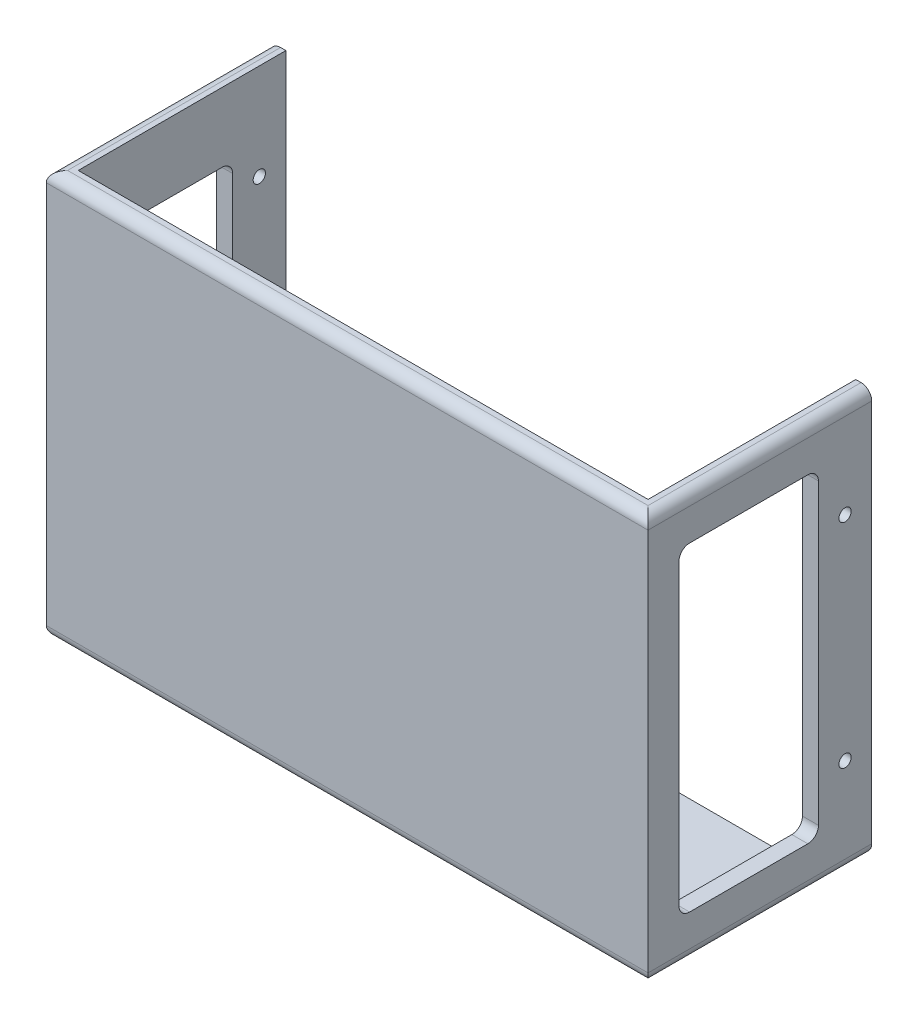
SolidWorks part; units mm, degrees
ref_plane "前视基准面" through (0, 0, 0) normal (0, 0, 1) x (1, 0, 0)
ref_plane "上视基准面" through (0, 0, 0) normal (0, 1, 0) x (1, 0, 0)
ref_plane "右视基准面" through (0, 0, 0) normal (1, 0, 0) x (0, 0, -1)
other "Configuration Table"
sketch "草图1" plane through (0, 0, 0) normal (0, 0, 1) x (1, 0, 0)
  line L0 (-56.5, 38) -> (56.5, 38)
  line L1 (-53.5, -35) -> (53.5, -35)
  line L2 (-53.5, -35) -> (-53.5, 35)
  line L3 (-53.5, 35) -> (53.5, 35)
  line L4 (53.5, -35) -> (53.5, 35)
  line L5 (-53.5, -35) -> (53.5, 35) construction
  line L6 (-53.5, 35) -> (53.5, -35) construction
  line L7 (56.5, -38) -> (56.5, 38)
  line L8 (-56.5, -38) -> (56.5, -38)
  line L9 (-56.5, -38) -> (-56.5, 38)
  point P0 (0, 0)
  dimension "D1" = 107
  dimension "D2" = 70
  dimension "D3" = 3
extrude "凸台-拉伸1" add sketch "草图1" along normal blind 40
sketch "草图2" plane through (0, 0, 40) normal (0, 0, 1) x (1, 0, 0)
  line L1 (-56.5, 38) -> (56.5, 38)
  line L2 (-56.5, 38) -> (-56.5, -38)
  line L3 (-56.5, -38) -> (56.5, -38)
  line L4 (56.5, 38) -> (56.5, -38)
extrude "凸台-拉伸2" add sketch "草图2" along normal blind 2
sketch "草图3" plane through (-56.5, 0, 0) normal (-1, 0, 0) x (0, 0, 1)
  line L0 (0, 0) -> (5, 0)
  line L1 (5, 0) -> (5, 20)
  circle A0 centre (5, 20) radius 1.05
  circle A1 centre (5, -20) radius 1.05
  dimension "D3" = 2.1
  dimension "D1" = 5
  dimension "D2" = 20
extrude "切除-拉伸1" cut sketch "草图3" against normal through all
sketch "草图6" plane through (0, 35, 0) normal (0, -1, 0) x (1, 0, 0)
  line L1 (-53.5, 0) -> (6.5, 0)
  line L2 (-53.5, 0) -> (-53.5, 30)
  line L3 (-53.5, 30) -> (6.5, 30)
  line L4 (6.5, 0) -> (6.5, 30)
  dimension "D1" = 30
  dimension "D2" = 60
extrude "切除-拉伸2" cut sketch "草图6" against normal through all
sketch "草图7" plane through (0, -35, 0) normal (0, 1, 0) x (1, 0, 0)
  line L0 (53.5, -40) -> (53.5, 0) construction
  line L1 (-53.5, 0) -> (53.5, 0)
  line L2 (-53.5, 0) -> (-53.5, -8.7913)
  line L3 (-53.5, -8.7913) -> (53.5, -8.7913)
  line L4 (53.5, 0) -> (53.5, -8.7913)
extrude "切除-拉伸3" cut sketch "草图7" against normal through all
sketch "草图9" plane through (56.5, 0, 0) normal (1, 0, 0) x (0, 0, -1)
  line L0 (-5, 20) -> (-10, 20)
  line L1 (-5, 20) -> (-5, 30)
  line L2 (-5, 30) -> (-10, 30)
  line L4 (-10, 30) -> (-36.2005, 30)
  line L5 (-10, 30) -> (-10, -30)
  line L6 (-10, -30) -> (-36.2005, -30)
  line L7 (-36.2005, 30) -> (-36.2005, -30)
  dimension "D1" = 5
  dimension "D2" = 10
  dimension "D3" = 60
extrude "切除-拉伸4" cut sketch "草图9" against normal blind 3 contours L4 L7 L6 L5
sketch "草图10" plane through (-56.5, 0, 0) normal (-1, 0, 0) x (0, 0, 1)
  line L0 (5, 20) -> (5, 25)
  line L1 (5, 25) -> (10, 25)
  line L3 (10, 25) -> (40, 25)
  line L4 (10, 25) -> (10, -25)
  line L5 (10, -25) -> (40, -25)
  line L6 (40, 25) -> (40, -25)
  dimension "D1" = 5
  dimension "D2" = 5
  dimension "D3" = 50
  dimension "D4" = 30
extrude "切除-拉伸5" cut sketch "草图10" against normal blind 3 contours L6 L3 L4 L5
sketch "草图13" plane through (0, 38, 0) normal (0, 1, 0) x (1, 0, 0)
  line L1 (-53.5, 0) -> (53.5, 0)
  line L2 (-53.5, 0) -> (-53.5, -40)
  line L3 (-53.5, -40) -> (53.5, -40)
  line L4 (53.5, 0) -> (53.5, -40)
  dimension "D1" = 107
  dimension "D2" = 40
extrude "切除-拉伸6" cut sketch "草图13" against normal blind 3
sketch "草图14" plane through (0, 0, 40) normal (0, 0, -1) x (-1, 0, 0)
  line L1 (-53.5, -35) -> (53.5, -35)
  line L2 (-53.5, -35) -> (-53.5, 38)
  line L3 (-53.5, 38) -> (53.5, 38)
  line L4 (53.5, -35) -> (53.5, 38)
sketch "草图17" plane through (0, 0, 40) normal (0, 0, -1) x (-1, 0, 0)
  line L1 (-56.5, 38) -> (56.5, 38)
  line L2 (-56.5, 38) -> (-56.5, -38)
  line L3 (-56.5, -38) -> (56.5, -38)
  line L4 (56.5, 38) -> (56.5, -38)
extrude "凸台-拉伸4" add sketch "草图17" along normal blind 1
sketch "草图18" plane through (0, 0, 8.7913) normal (0, 0, -1) x (-1, 0, 0)
  line L1 (-53.5, -35) -> (53.5, -35)
  line L2 (-53.5, -35) -> (-53.5, -38)
  line L3 (-53.5, -38) -> (53.5, -38)
  line L4 (53.5, -35) -> (53.5, -38)
extrude "切除-拉伸7" cut sketch "草图18" against normal blind 2
fillet "圆角1" radius 2 14 edges at (55, 30, 10) (55, 30, 36.2005) (55, -30, 36.2005) (55, -30, 10) (-55, 25, 10) (-55, 25, 39) (-55, -25, 10) (-55, -25, 39) (0, 38, 42) (56.5, 38, 21) (-56.5, 38, 21) (-56.5, -38, 21) (0, -38, 42) (56.5, -38, 21)
sketch "草图19" plane through (56.5, 0, 0) normal (1, 0, 0) x (0, 0, -1)
  circle A0 centre (-5, 20) radius 1.15
  circle A1 centre (-5, -20) radius 1.15
  dimension "D1" = 2.3
  dimension "D2" = 2.3
extrude "切除-拉伸8" cut sketch "草图19" against normal through all
